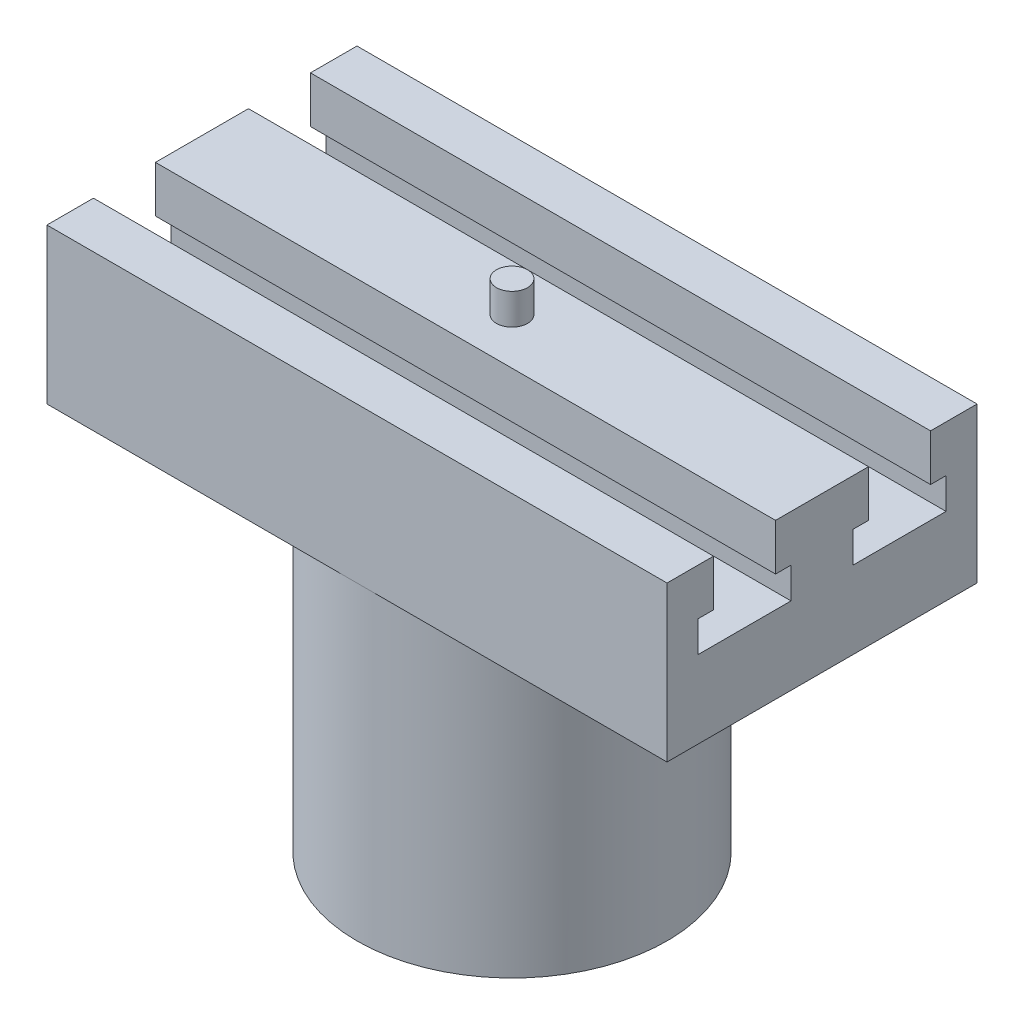
SolidWorks part; units mm, degrees
material "1060 Alloy"
ref_plane "Front Plane" through (0, 0, 0) normal (0, 0, 1) x (1, 0, 0)
ref_plane "Top Plane" through (0, 0, 0) normal (0, 1, 0) x (1, 0, 0)
ref_plane "Right Plane" through (0, 0, 0) normal (1, 0, 0) x (0, 0, -1)
sketch "Sketch2" plane through (0, 0, 0) normal (0, 1, 0) x (1, 0, 0)
  circle A0 centre (0, 0) radius 50
  dimension "D1" = 100
extrude "Boss-Extrude1" add sketch "Sketch2" along normal blind 100
sketch "Sketch3" plane through (0, 100, 0) normal (0, 1, 0) x (1, 0, 0)
  line L1 (-100, 50) -> (100, 50)
  line L2 (-100, 50) -> (-100, -50)
  line L3 (-100, -50) -> (100, -50)
  line L4 (100, 50) -> (100, -50)
  line L5 (-100, 50) -> (100, -50) construction
  line L6 (-100, -50) -> (100, 50) construction
  point P0 (0, 0)
  dimension "D1" = 100
  dimension "D2" = 200
extrude "Boss-Extrude2" add sketch "Sketch3" along normal blind 50
sketch "Sketch4" plane through (100, 0, 0) normal (1, 0, 0) x (0, 0, -1)
  line L0 (0, 150) -> (0, 100) construction
  line L1 (-50, 150) -> (50, 150) construction
  line L2 (-50, 100) -> (50, 100) construction
  line L3 (-50, 125) -> (0, 125) construction
  line L4 (-50, 150) -> (-50, 100) construction
  line L5 (-25, 125) -> (-25, 150) construction
  line L6 (-35, 150) -> (-35, 135)
  line L7 (-35, 135) -> (-40, 135)
  line L8 (-40, 135) -> (-40, 125)
  line L9 (-40, 125) -> (-10, 125)
  line L10 (-35, 150) -> (-15, 150)
  line L11 (-10, 135) -> (-10, 125)
  line L12 (-15, 135) -> (-10, 135)
  line L13 (-15, 150) -> (-15, 135)
  line L14 (40, 135) -> (40, 125)
  line L15 (35, 135) -> (40, 135)
  line L16 (35, 150) -> (35, 135)
  line L17 (35, 150) -> (15, 150)
  line L18 (15, 150) -> (15, 135)
  line L19 (15, 135) -> (10, 135)
  line L20 (10, 135) -> (10, 125)
  line L21 (40, 125) -> (10, 125)
  dimension "D1" = 15
  dimension "D2" = 15
  dimension "D3" = 10
extrude "Cut-Extrude1" cut sketch "Sketch4" against normal through all
sketch "Sketch5" plane through (0, 150, 0) normal (0, 1, 0) x (1, 0, 0)
  circle A0 centre (0, 0) radius 5
  dimension "D1" = 10
extrude "Boss-Extrude3" add sketch "Sketch5" along normal blind 10
